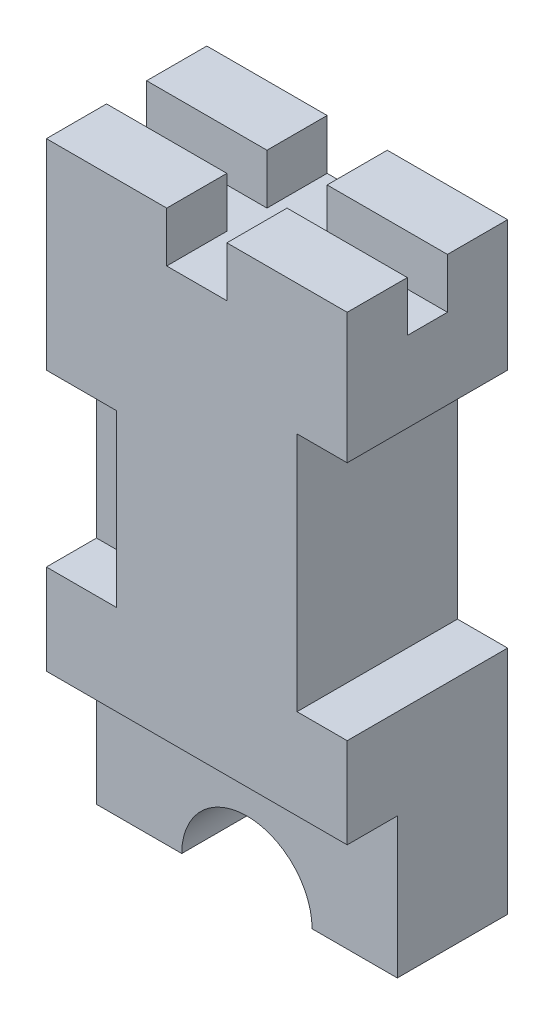
SolidWorks part; units mm, degrees
ref_plane "Спереди" through (0, 0, 0) normal (0, 0, 1) x (1, 0, 0)
ref_plane "Сверху" through (0, 0, 0) normal (0, 1, 0) x (1, 0, 0)
ref_plane "Справа" through (0, 0, 0) normal (1, 0, 0) x (0, 0, -1)
sketch "Эскиз1" plane through (0, 0, 0) normal (0, 0, 1) x (1, 0, 0)
  line L1 (-15, -30) -> (15, -30)
  line L2 (-15, -30) -> (-15, 30)
  line L3 (-15, 30) -> (15, 30)
  line L4 (15, -30) -> (15, 30)
  line L5 (-15, -30) -> (15, 30) construction
  line L6 (-15, 30) -> (15, -30) construction
  point P0 (0, 0)
  dimension "D1" = 30
  dimension "D2" = 60
extrude "Бобышка-Вытянуть1" add sketch "Эскиз1" along normal blind 16
sketch "Эскиз2" plane through (-15, 0, 0) normal (-1, 0, 0) x (0, 0, 1)
  line L0 (8, 30) -> (8, -30) construction
  line L1 (16, 30) -> (0, 30) construction
  line L2 (16, -30) -> (0, -30) construction
  line L4 (6, 25) -> (10, 25)
  line L5 (6, 25) -> (6, 30)
  line L6 (6, 30) -> (10, 30)
  line L7 (10, 25) -> (10, 30)
  line L8 (6, 25) -> (10, 30) construction
  line L9 (6, 30) -> (10, 25) construction
  line L10 (16, -30) -> (11, -30)
  line L11 (16, -30) -> (16, -16)
  line L12 (16, -16) -> (11, -16)
  line L13 (11, -30) -> (11, -16)
  point P6 (8, 27.5)
  dimension "D1" = 4
  dimension "D2" = 5
  dimension "D3" = 5
  dimension "D4" = 14
extrude "Вырез-Вытянуть1" cut sketch "Эскиз2" against normal through all
sketch "Эскиз3" plane through (0, 0, 16) normal (0, 0, 1) x (1, 0, 0)
  line L0 (0, -30) -> (0, 30) construction
  line L1 (-15, -30) -> (15, -30) construction
  line L2 (15, 30) -> (-15, 30) construction
  line L4 (-3, 25) -> (3, 25)
  line L5 (-3, 25) -> (-3, 30)
  line L6 (-3, 30) -> (3, 30)
  line L7 (3, 25) -> (3, 30)
  line L8 (-3, 25) -> (3, 30) construction
  line L9 (-3, 30) -> (3, 25) construction
  circle A0 centre (0, -30) radius 6.5
  point P5 (0, 27.5)
  dimension "D3" = 13
  dimension "D1" = 6
  dimension "D2" = 5
extrude "Вырез-Вытянуть2" cut sketch "Эскиз3" against normal through all
sketch "Эскиз4" plane through (0, 0, 16) normal (0, 0, 1) x (1, 0, 0)
  line L0 (15, -16) -> (15, 30) construction
  line L1 (15, -7) -> (10, -7)
  line L2 (15, -7) -> (15, 10)
  line L3 (15, 10) -> (10, 10)
  line L4 (10, -7) -> (10, 10)
  line L5 (15, -16) -> (-15, -16) construction
  line L6 (15, 30) -> (3, 30) construction
  dimension "D1" = 5
  dimension "D2" = 9
  dimension "D3" = 20
extrude "Вырез-Вытянуть3" cut sketch "Эскиз4" against normal through all
sketch "Эскиз5" plane through (0, 0, 16) normal (0, 0, 1) x (1, 0, 0)
  line L0 (-15, 30) -> (-15, -16) construction
  line L1 (-15, -7) -> (-8, -7)
  line L2 (-15, -7) -> (-15, 10)
  line L3 (-15, 10) -> (-8, 10)
  line L4 (-8, -7) -> (-8, 10)
  line L5 (15, 10) -> (10, 10) construction
  line L6 (10, -7) -> (15, -7) construction
  dimension "D1" = 7
extrude "Вырез-Вытянуть4" cut sketch "Эскиз5" against normal blind 5
sketch "Эскиз6" plane through (0, 10, 0) normal (0, -1, 0) x (1, 0, 0)
  line L4 (15, 16) -> (10, 16)
  line L5 (10, 16) -> (10, 0)
  line L6 (10, 0) -> (15, 0)
  line L7 (15, 0) -> (15, 16)
  line L8 (15, 16) -> (10, 16)
  line L9 (10, 16) -> (10, 0)
  line L10 (10, 0) -> (15, 0)
  line L11 (15, 0) -> (15, 16)
  dimension "D1" = 0
extrude "Вырез-Вытянуть5" cut sketch "Эскиз6" against normal blind 7
